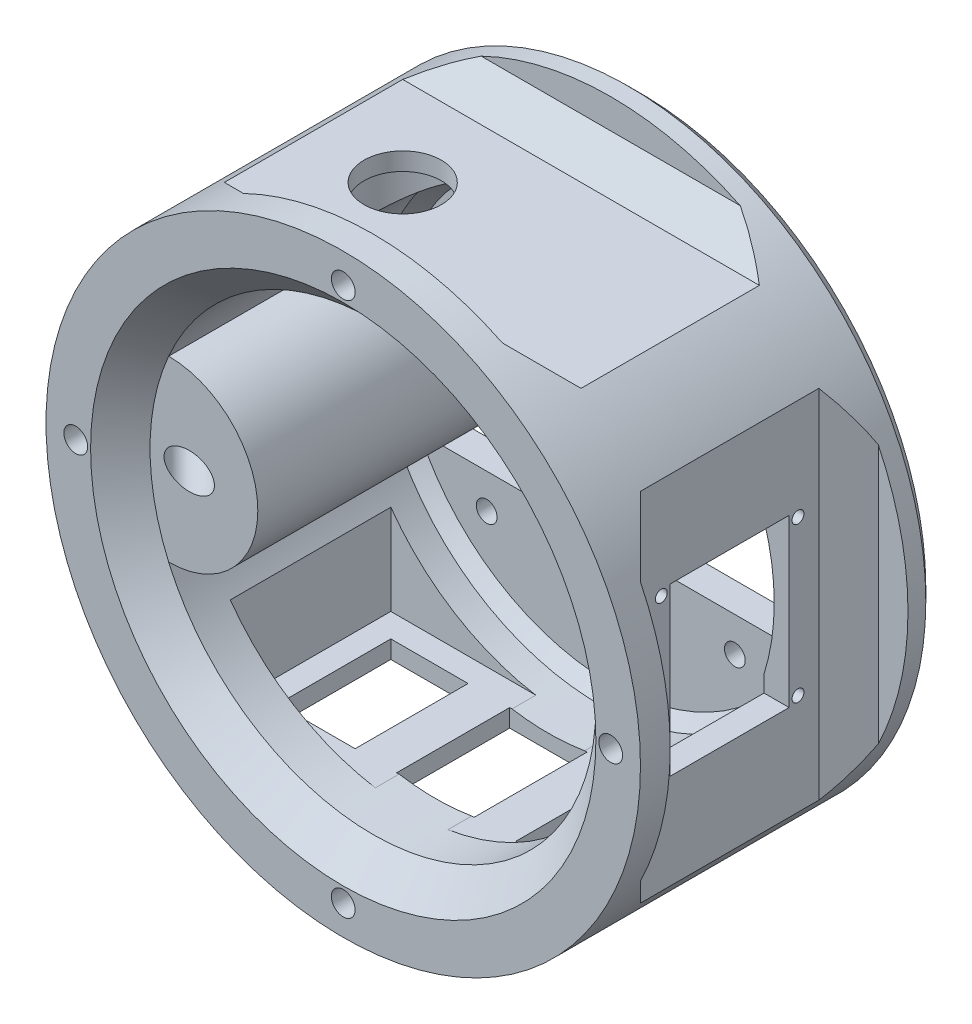
SolidWorks part; units mm, degrees
ref_plane "Plan de face" through (0, 0, 0) normal (0, 0, 1) x (1, 0, 0)
ref_plane "Plan de dessus" through (0, 0, 0) normal (0, 1, 0) x (1, 0, 0)
ref_plane "Plan de droite" through (0, 0, 0) normal (1, 0, 0) x (0, 0, -1)
sketch "Esquisse1" plane through (0, 0, 0) normal (0, 0, 1) x (1, 0, 0)
  circle A0 centre (0, 0) radius 50
  dimension "D1" = 100
extrude "Boss.-Extru.1" add sketch "Esquisse1" along normal blind 50
ref_plane "Plan1" through (0, 50, 0) normal (0, 1, 0) x (1, 0, 0)
sketch "Esquisse3" plane through (0, 50, 0) normal (0, 1, 0) x (1, 0, 0)
  line L0 (0, 0) -> (0, -50)
  line L1 (-50, -50) -> (50, -50) construction
  line L3 (45, -45) -> (-45, -45)
  line L4 (45, -45) -> (45, -5)
  line L5 (45, -5) -> (-45, -5)
  line L6 (-45, -45) -> (-45, -5)
  line L7 (45, -45) -> (-45, -5) construction
  line L8 (45, -5) -> (-45, -45) construction
  point P5 (0, -25)
  dimension "D1" = 90
  dimension "D2" = 40
extrude "Enlèv. mat.-Extru.1" cut sketch "Esquisse3" against normal blind 10 contours L6 L3 L0 L5 | L4 L5 L0 L3
pattern_circular "Répétition circulaire1" count 4 over 360 about axis through (0, 0, 0) along (0, 0, 1) of "Enlèv. mat.-Extru.1"
chamfer "Chanfrein1" distance 5 angle 45 8 edges at (0, 40, 45) (40, 0, 45) (40, 0, 5) (0, -40, 5) (-40, 0, 5) (0, -40, 45) (-40, 0, 45) (0, 40, 5)
ref_plane "Plan2" through (-2.5, 0, -2.5) normal (-0.7071, 0, -0.7071) x (-0.7071, 0, 0.7071)
sketch "Esquisse11" plane through (-2.5, 0, -2.5) normal (-0.7071, 0, -0.7071) x (-0.7071, 0, 0.7071)
  circle A0 centre (53.6751, 0) radius 13.5
  ellipse E0 centre (31.8198, 0) end of major axis (31.8198, 50) minor radius 35.3553 (63.6396, -21.7945) -> (63.6396, 21.7945) ccw construction
  point P11 (67.1751, 0)
  dimension "D1" = 27
extrude "Boss.-Extru.3" add sketch "Esquisse11" against normal blind 5
sketch "Esquisse4" plane through (0, 0, 0) normal (0, 0, -1) x (-1, 0, 0)
  circle A0 centre (0, 0) radius 37.5
  dimension "D1" = 75
extrude "Enlèv. mat.-Extru.2" cut sketch "Esquisse4" against normal up to surface (50 mm away) up to face at (50, 0, 50)
chamfer "Chanfrein2" distance 5 angle 45 1 edges at (37.5, 0, 50)
sketch "Esquisse6" plane through (0, 0, 0) normal (0, 0, -1) x (-1, 0, 0)
  line L0 (-34.3693, 15) -> (34.3693, 15)
  line L1 (-34.3693, -15) -> (34.3693, -15)
  circle A0 centre (0, 0) radius 37.5 construction
  circle A1 centre (0, 0) radius 37.5
  circle M4 centre (0, 0) radius 37.5
  dimension "D1" = 15
  dimension "D2" = 15
extrude "Boss.-Extru.2" add sketch "Esquisse6" against normal blind 5 contours L0 M4 | L1 M4
sketch "Esquisse5" plane through (0, 0, 0) normal (0, 0, -1) x (-1, 0, 0)
  circle A0 centre (0, 0) radius 29.5 construction
  circle A1 centre (-20.875, 20.8443) radius 1.75
  circle A2 centre (20.875, 20.8443) radius 1.75
  circle A3 centre (-20.875, -20.8443) radius 1.75
  circle A4 centre (20.875, -20.8443) radius 1.75
  dimension "D1" = 59
  dimension "D2" = 3.5
  dimension "D3" = 41.75
  dimension "D4" = 41.6886
extrude "Enlèv. mat.-Extru.3" cut sketch "Esquisse5" against normal up to surface (5 mm away) up to face at (0, 26.25, 5)
sketch "Esquisse7" plane through (0, 0, 50) normal (0, 0, 1) x (1, 0, 0)
  circle A0 centre (-45, 0) radius 2
  point P4 (0, 0)
  point P5 (0, 0)
  point P6 (0, 0)
  dimension "D1" = 4
  dimension "D2" = 45
extrude "Enlèv. mat.-Extru.4" cut sketch "Esquisse7" against normal blind 6
pattern_circular "Répétition circulaire2" count 4 over 360 about axis through (0, 0, 0) along (0, 0, 1) of "Enlèv. mat.-Extru.4"
chamfer "Chanfrein3" distance 2 angle 45 2 edges at (0, 37.5, 5) (0, -37.5, 5)
sketch "Esquisse8" plane through (0, -40, 0) normal (0, -1, 0) x (1, 0, 0)
  line L0 (-30, 25) -> (30, 25) construction
  line L1 (-13.5, 15.5) -> (-26.5, 15.5)
  line L2 (-13.5, 15.5) -> (-13.5, 34.5)
  line L3 (-13.5, 34.5) -> (-26.5, 34.5)
  line L4 (-26.5, 15.5) -> (-26.5, 34.5)
  line L5 (-13.5, 15.5) -> (-26.5, 34.5) construction
  line L6 (-13.5, 34.5) -> (-26.5, 15.5) construction
  line L7 (-30, 40) -> (-30, 10) construction
  line L8 (30, 10) -> (30, 40) construction
  line L9 (6.5, 15.5) -> (6.5, 34.5)
  line L10 (6.5, 15.5) -> (-6.5, 15.5)
  line L11 (-6.5, 15.5) -> (-6.5, 34.5)
  line L12 (6.5, 34.5) -> (-6.5, 34.5)
  line L13 (26.5, 15.5) -> (26.5, 34.5)
  line L14 (26.5, 15.5) -> (13.5, 15.5)
  line L15 (13.5, 15.5) -> (13.5, 34.5)
  line L16 (26.5, 34.5) -> (13.5, 34.5)
  line L17 (20, 15.5) -> (20, 34.5) construction
  point P0 (-20, 25)
  dimension "D1" = 13
  dimension "D2" = 19
  dimension "D3" = 10
  dimension "D5" = 10
  dimension "D4" = 3
extrude "Enlèv. mat.-Extru.5" cut sketch "Esquisse8" against normal blind 19
sketch "Esquisse9" plane through (26.5, 0, 0) normal (-1, 0, 0) x (0, 0, 1)
  line L1 (15.5, -37) -> (34.5, -37)
  line L5 (34.5, -26.533) -> (15.5, -26.533)
  line L6 (15.5, -26.533) -> (15.5, -40)
  line L7 (15.5, -40) -> (34.5, -40)
  line L8 (34.5, -40) -> (34.5, -26.533)
  line L10 (15.5, -26.533) -> (15.5, -40)
  line L11 (15.5, -40) -> (34.5, -40)
  line L12 (34.5, -40) -> (34.5, -26.533)
  line L13 (34.5, -26.533) -> (15.5, -26.533)
  line M5 (15.5, -26.533) -> (15.5, -40)
  line M7 (34.5, -40) -> (34.5, -26.533)
  line M8 (34.5, -26.533) -> (15.5, -26.533)
  dimension "D2" = 3
  dimension "D1" = 0
extrude "Enlèv. mat.-Extru.6" cut sketch "Esquisse9" along normal up to surface (53 mm away) contours L1 M5 M7 M8 up to face at (-26.5, -33.2665, 25)
sketch "Esquisse10" plane through (0, -37, 0) normal (0, 1, 0) x (1, 0, 0)
  line L12 (30.5, -38.5) -> (30.5, -11.5)
  line L13 (30.5, -11.5) -> (-30.5, -11.5)
  line L14 (-30.5, -38.5) -> (30.5, -38.5)
  line L15 (-30.5, -11.5) -> (-30.5, -38.5)
  line L16 (30.5, -38.5) -> (30.5, -11.5)
  line L17 (30.5, -11.5) -> (-30.5, -11.5)
  line L18 (-30.5, -38.5) -> (30.5, -38.5)
  line L19 (-30.5, -11.5) -> (-30.5, -38.5)
  dimension "D1" = 4
extrude "Enlèv. mat.-Extru.8" cut sketch "Esquisse10" along normal blind 19
sketch "Esquisse12" plane through (-2.5, 0, -2.5) normal (-0.7071, 0, -0.7071) x (-0.7071, 0, 0.7071)
  circle A0 centre (53.6751, 0) radius 13.5
  arc A1 (67.1751, 0) -> (53.033, 13.4847) centre (53.6751, 0) ccw construction
sketch "Esquisse14" plane through (0, 0, 0) normal (0, 0, -1) x (-1, 0, 0)
  arc A0 (34.3693, 15) -> (34.3693, -15) centre (34.3693, 0) ccw
  arc A1 (34.3693, -15) -> (34.3693, 15) centre (0, 0) ccw construction
  arc A2 (34.3693, -15) -> (34.3693, 15) centre (0, 0) ccw
  dimension "D1" = 15
extrude "Boss.-Extru.4" add sketch "Esquisse14" against normal blind 45 contours A0 A2
extrude "Enlèv. mat.-Extru.10" cut sketch "Esquisse12" along normal blind 17
sketch "Esquisse15" plane through (-2.5, 0, -2.5) normal (-0.7071, 0, -0.7071) x (-0.7071, 0, 0.7071)
  circle A0 centre (53.6751, 0) radius 3
  arc A1 (53.033, 13.4847) -> (53.033, -13.4847) centre (53.6751, 0) ccw construction
  point P2 (54.9028, 0)
  point P3 (0, 0)
  dimension "D1" = 6
extrude "Enlèv. mat.-Extru.11" cut sketch "Esquisse15" against normal blind 17 contours A0
sketch "Esquisse16" plane through (-2.5, 0, -2.5) normal (-0.7071, 0, -0.7071) x (-0.7071, 0, 0.7071)
  circle A0 centre (53.6751, 0) radius 12
  circle A1 centre (53.6751, 0) radius 3 construction
  dimension "D1" = 24
extrude "Enlèv. mat.-Extru.12" cut sketch "Esquisse16" against normal blind 1
chamfer "Chanfrein4" distance 7 angle 45 1 edges at (37.5, 0, 0)
chamfer "Chanfrein5" distance 2 angle 45 1 edges at (50, 0, 0)
sketch "Esquisse17" plane through (40, 0, 0) normal (1, 0, 0) x (0, 0, -1)
  line L0 (-40, 0) -> (-10, 0) construction
  line L1 (-15, -14) -> (-35, -14)
  line L2 (-15, -14) -> (-15, 14)
  line L3 (-15, 14) -> (-35, 14)
  line L4 (-35, -14) -> (-35, 14)
  line L5 (-15, -14) -> (-35, 14) construction
  line L6 (-15, 14) -> (-35, -14) construction
  line L7 (-40, 30) -> (-40, -30) construction
  line L8 (-10, -30) -> (-10, 30) construction
  point P0 (-25, 0)
  point P11 (0, 0)
  dimension "D1" = 20
  dimension "D2" = 28
extrude "Enlèv. mat.-Extru.13" cut sketch "Esquisse17" against normal blind 6
ref_plane "Plan3" through (34.7886, 0, 0) normal (1, 0, 0) x (0, 0, -1)
sketch "Esquisse18" plane through (34.7886, 0, 0) normal (1, 0, 0) x (0, 0, -1)
  line L14 (-10, -19) -> (-10, 19)
  line L15 (-40, -19) -> (-10, -19)
  line L16 (-10, 19) -> (-40, 19)
  line L17 (-40, 19) -> (-40, -19)
  line L18 (-10, -19) -> (-10, 19)
  line L19 (-40, -19) -> (-10, -19)
  line L20 (-10, 19) -> (-40, 19)
  line L21 (-40, 19) -> (-40, -19)
  dimension "D1" = 5
extrude "Enlèv. mat.-Extru.14" cut sketch "Esquisse18" against normal blind 6 and the other way blind 1
sketch "Esquisse19" plane through (40, 0, 0) normal (1, 0, 0) x (0, 0, -1)
  line L0 (-25, 30) -> (-25, -30) construction
  line L1 (-10, 30) -> (-40, 30) construction
  line L2 (-40, -30) -> (-10, -30) construction
  line L3 (-35, -14) -> (-40, -14) construction
  line L4 (-40, 30) -> (-40, -30) construction
  circle A0 centre (-36.5, -13) radius 1
  circle A1 centre (-13.5, -13) radius 1
  point P8 (-40, -14)
  dimension "D2" = 2
  dimension "D1" = 11.5
extrude "Enlèv. mat.-Extru.15" cut sketch "Esquisse19" against normal blind 6
mirror "Symétrie1" about plane through (0, 0, 0) normal (0, 1, 0) of "Enlèv. mat.-Extru.15"
sketch "Esquisse20" plane through (0, 40, 0) normal (0, 1, 0) x (1, 0, 0)
  line L0 (-30, -25) -> (30, -25) construction
  line L1 (-30, -10) -> (-30, -40) construction
  line L2 (30, -40) -> (30, -10) construction
  circle A0 centre (-15, -25) radius 6.5
  point P8 (0, 0)
  point P9 (-18.0289, -25)
  dimension "D1" = 13
  dimension "D2" = 15
extrude "Enlèv. mat.-Extru.16" cut sketch "Esquisse20" against normal blind 13
ref_plane "Plan4" through (0, 29, 0) normal (0, 1, 0) x (1, 0, 0)
sketch "Esquisse21" plane through (0, 29, 0) normal (0, 1, 0) x (1, 0, 0)
  circle A2 centre (-15, -25) radius 11.5
  circle A3 centre (-15, -25) radius 11.5
  dimension "D1" = 5
extrude "Enlèv. mat.-Extru.17" cut sketch "Esquisse21" along normal blind 8 and the other way blind 8
equation "\"éà\"=11.1716"
